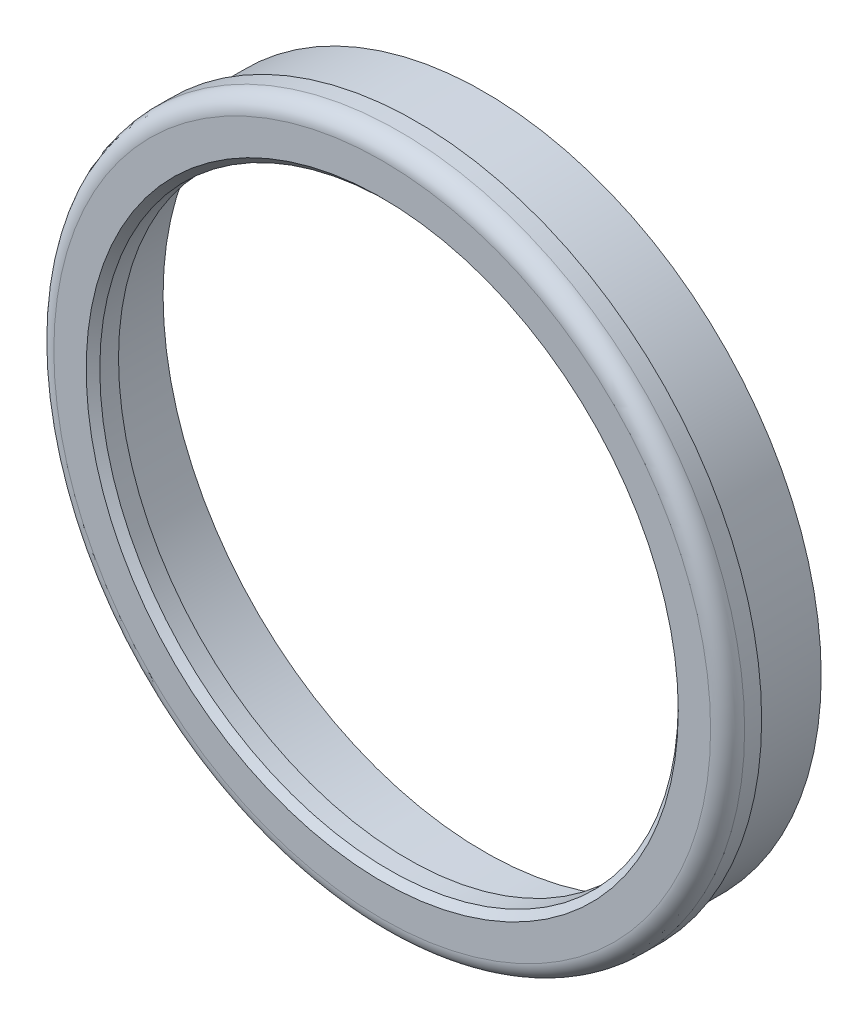
SolidWorks part; units mm, degrees
ref_plane "Front Plane" through (0, 0, 0) normal (0, 0, 1) x (1, 0, 0)
ref_plane "Top Plane" through (0, 0, 0) normal (0, 1, 0) x (1, 0, 0)
ref_plane "Right Plane" through (0, 0, 0) normal (1, 0, 0) x (0, 0, -1)
sketch "Sketch1" plane through (0, 0, 0) normal (0, 0, 1) x (1, 0, 0)
  circle A0 centre (0, 0) radius 20.3
  circle A1 centre (0, 0) radius 17
  dimension "D1" = 34
  dimension "D2" = 40.6
extrude "Boss-Extrude1" add sketch "Sketch1" against normal blind 2
sketch "Sketch2" plane through (0, 0, -2) normal (0, 0, -1) x (-1, 0, 0)
  circle A0 centre (0, 0) radius 18.88
  circle A1 centre (0, 0) radius 19.8
  dimension "D1" = 39.6
  dimension "D2" = 37.76
extrude "Boss-Extrude2" add sketch "Sketch2" along normal blind 4
chamfer "Chamfer2" distance 0.4 angle 45 1 edges at (17, 0, 0)
sketch "Sketch3" plane through (0, 0, -2) normal (0, 0, -1) x (-1, 0, 0)
  circle A0 centre (0, 0) radius 18.88
  dimension "D1" = 37.76
extrude "Cut-Extrude1" cut sketch "Sketch3" against normal blind 0.5
fillet "Fillet1" radius 1 1 edges at (20.3, 0, 0)
